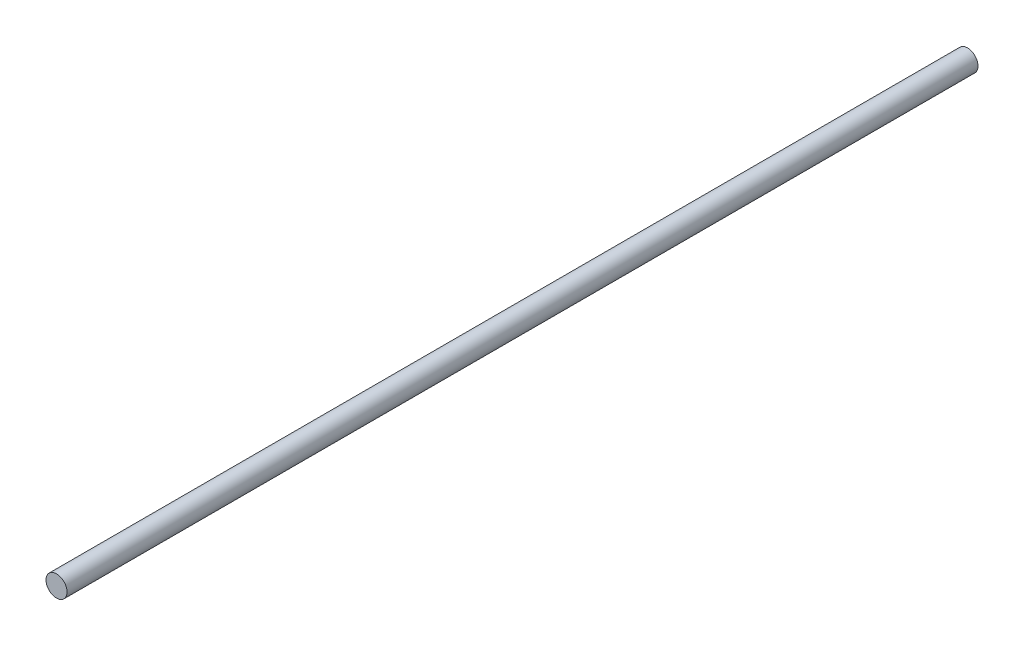
SolidWorks part; units mm, degrees
ref_plane "前视基准面" through (0, 0, 0) normal (0, 0, 1) x (1, 0, 0)
ref_plane "上视基准面" through (0, 0, 0) normal (0, 1, 0) x (1, 0, 0)
ref_plane "右视基准面" through (0, 0, 0) normal (1, 0, 0) x (0, 0, -1)
sketch "草图1" plane through (0, 0, 0) normal (0, 0, 1) x (1, 0, 0)
  circle A0 centre (0, 0) radius 2
  dimension "D1" = 4
extrude "凸台-拉伸1" add sketch "草图1" along normal blind 173
